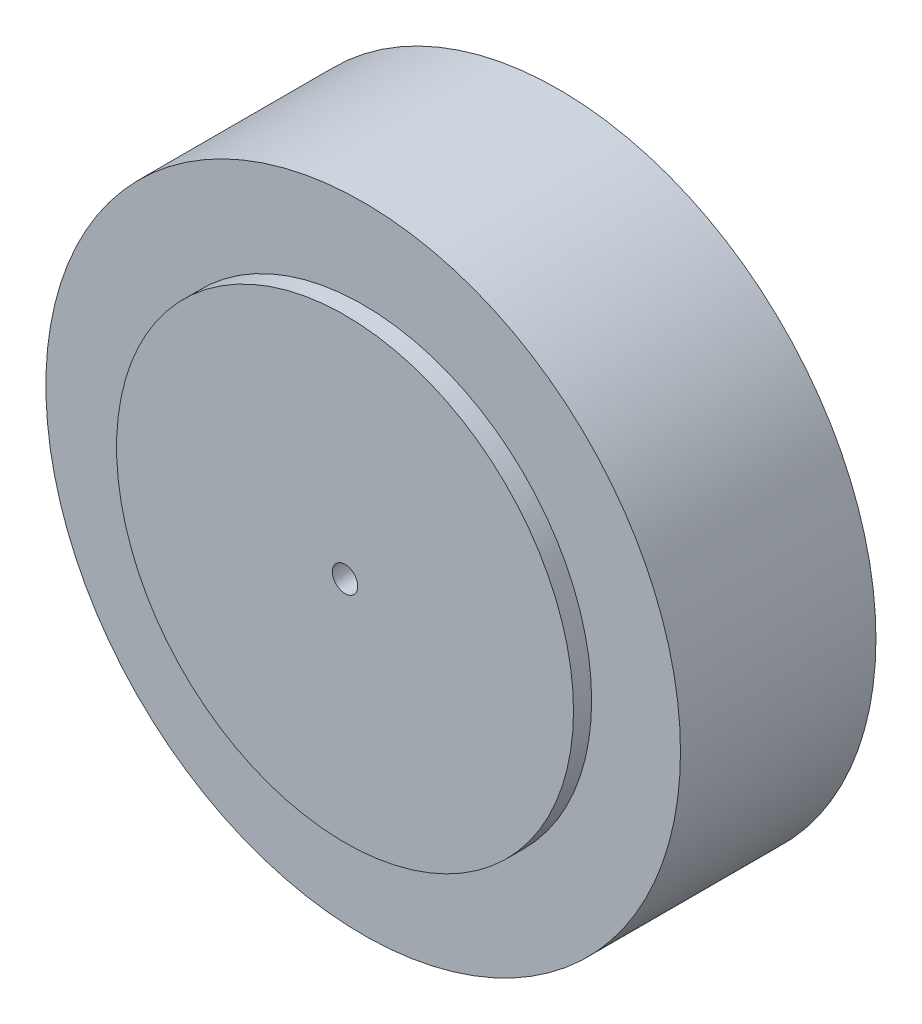
SolidWorks part; units mm, degrees
ref_plane "Front Plane" through (0, 0, 0) normal (0, 0, 1) x (1, 0, 0)
ref_plane "Top Plane" through (0, 0, 0) normal (0, 1, 0) x (1, 0, 0)
ref_plane "Right Plane" through (0, 0, 0) normal (1, 0, 0) x (0, 0, -1)
sketch "Sketch1" plane through (0, 0, 0) normal (0, 0, 1) x (1, 0, 0)
  circle A0 centre (0, 0) radius 31.75
  circle A1 centre (0, 0) radius 1.27
  dimension "D1" = 63.5
  dimension "D2" = 2.54
extrude "Boss-Extrude1" add sketch "Sketch1" along normal blind 19.558
sketch "Sketch2" plane through (0, 0, 19.558) normal (0, 0, 1) x (1, 0, 0)
  circle A0 centre (0, 0) radius 22.86
  circle A1 centre (0, 0) radius 1.27
  dimension "D1" = 45.72
  dimension "D2" = 2.54
extrude "Boss-Extrude2" add sketch "Sketch2" along normal blind 1.8161
